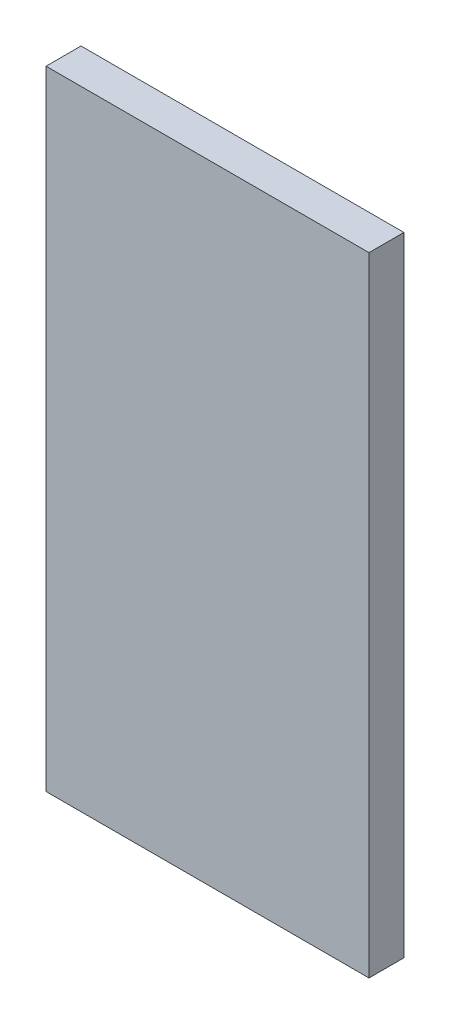
SolidWorks part; units mm, degrees
ref_plane "Front Plane" through (0, 0, 0) normal (0, 0, 1) x (1, 0, 0)
ref_plane "Top Plane" through (0, 0, 0) normal (0, 1, 0) x (1, 0, 0)
ref_plane "Right Plane" through (0, 0, 0) normal (1, 0, 0) x (0, 0, -1)
sketch "Sketch1" plane through (0, 0, 0) normal (0, 0, 1) x (1, 0, 0)
  line L1 (0, 0) -> (73, 0)
  line L2 (0, 0) -> (0, 142)
  line L3 (0, 142) -> (73, 142)
  line L4 (73, 0) -> (73, 142)
  dimension "D1" = 73
  dimension "D2" = 142
extrude "Boss-Extrude1" add sketch "Sketch1" along normal blind 7.9
